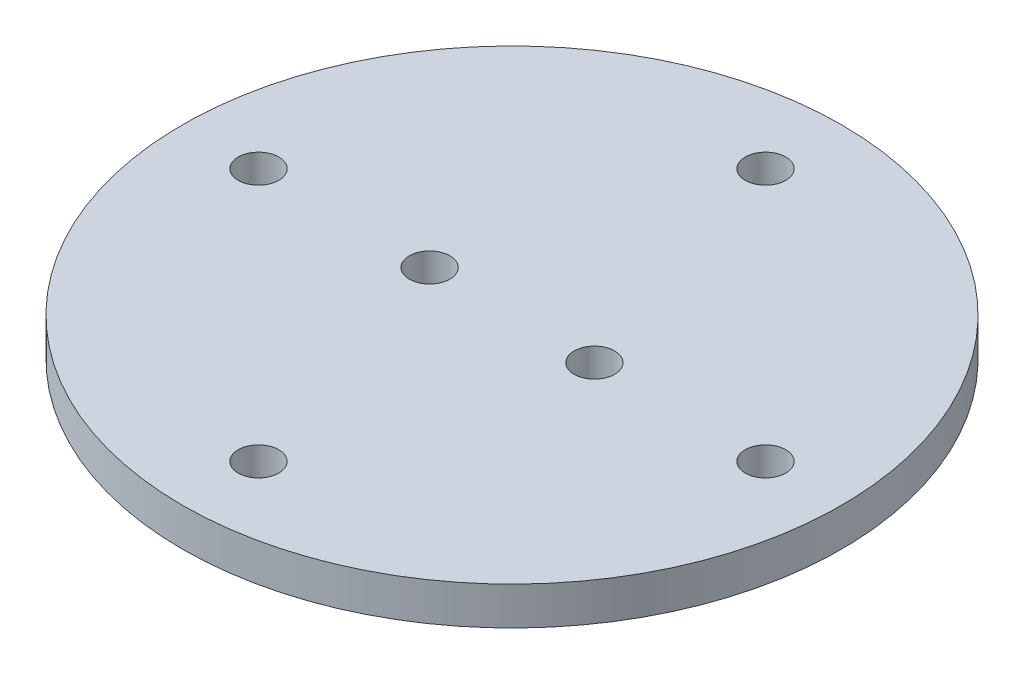
SolidWorks part; units mm, degrees
material "Thornel Mat VMA"
ref_plane "前视基准面" through (0, 0, 0) normal (0, 0, 1) x (1, 0, 0)
ref_plane "上视基准面" through (0, 0, 0) normal (0, 1, 0) x (1, 0, 0)
ref_plane "右视基准面" through (0, 0, 0) normal (1, 0, 0) x (0, 0, -1)
other "Configuration Table"
sketch "草图1" plane through (0, 0, 0) normal (0, 1, 0) x (1, 0, 0)
  line L0 (-37.7957, 0) -> (37.908, 0) construction
  line L1 (0, 36.5321) -> (0, -35.2404) construction
  circle A0 centre (0, 0) radius 26
  circle A1 centre (0, 0) radius 6.5 construction
  circle A2 centre (-6.5, 0) radius 1.6
  circle A3 centre (6.5, 0) radius 1.6
  circle A4 centre (0, 0) radius 20 construction
  circle A5 centre (-20, 0) radius 1.6
  circle A6 centre (0, 20) radius 1.6
  circle A7 centre (20, 0) radius 1.6
  circle A8 centre (0, -20) radius 1.6
  dimension "D1" = 13
  dimension "D2" = 3.2
  dimension "D3" = 52
  dimension "D4" = 40
  dimension "D5" = 3.2
extrude "凸台-拉伸1" add sketch "草图1" along normal blind 3
